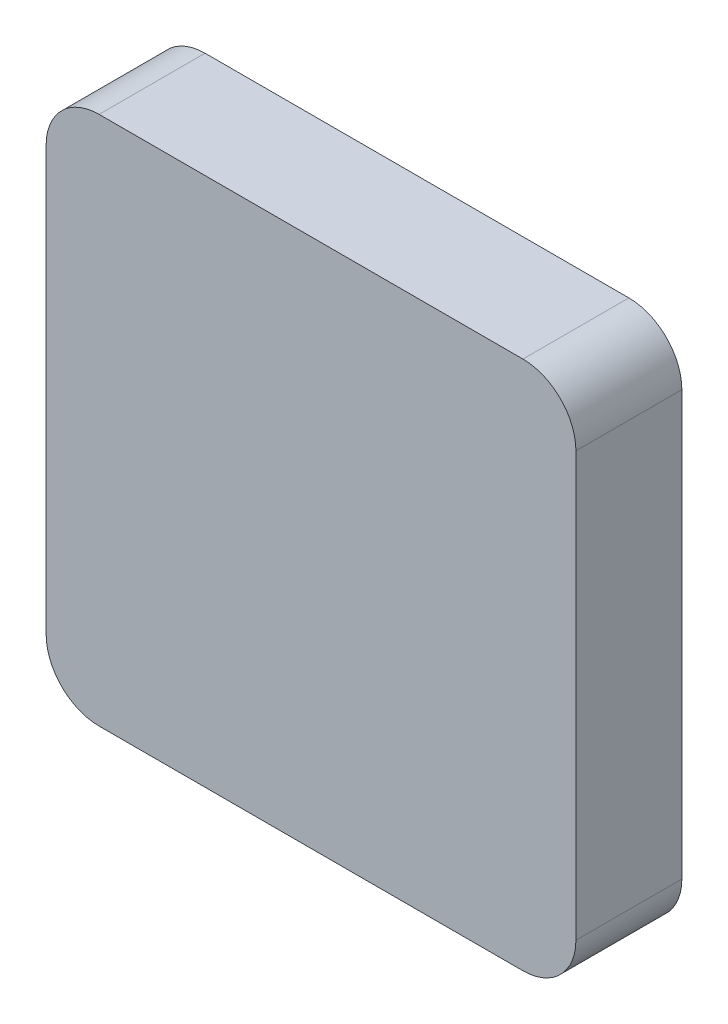
SolidWorks part; units mm, degrees
ref_plane "Front Plane" through (0, 0, 0) normal (0, 0, 1) x (1, 0, 0)
ref_plane "Top Plane" through (0, 0, 0) normal (0, 1, 0) x (1, 0, 0)
ref_plane "Right Plane" through (0, 0, 0) normal (1, 0, 0) x (0, 0, -1)
sketch "Sketch1" plane through (0, 0, 0) normal (0, 0, 1) x (1, 0, 0)
  line L1 (-25, -25) -> (25, -25)
  line L2 (-25, -25) -> (-25, 25)
  line L3 (-25, 25) -> (25, 25)
  line L4 (25, -25) -> (25, 25)
  line L5 (-25, -25) -> (25, 25) construction
  line L6 (-25, 25) -> (25, -25) construction
  point P0 (0, 0)
  dimension "D1" = 50
  dimension "D2" = 50
extrude "Boss-Extrude1" add sketch "Sketch1" along normal blind 10
fillet "Fillet1" radius 5 4 edges at (25, -25, 5) (-25, -25, 5) (-25, 25, 5) (25, 25, 5)
